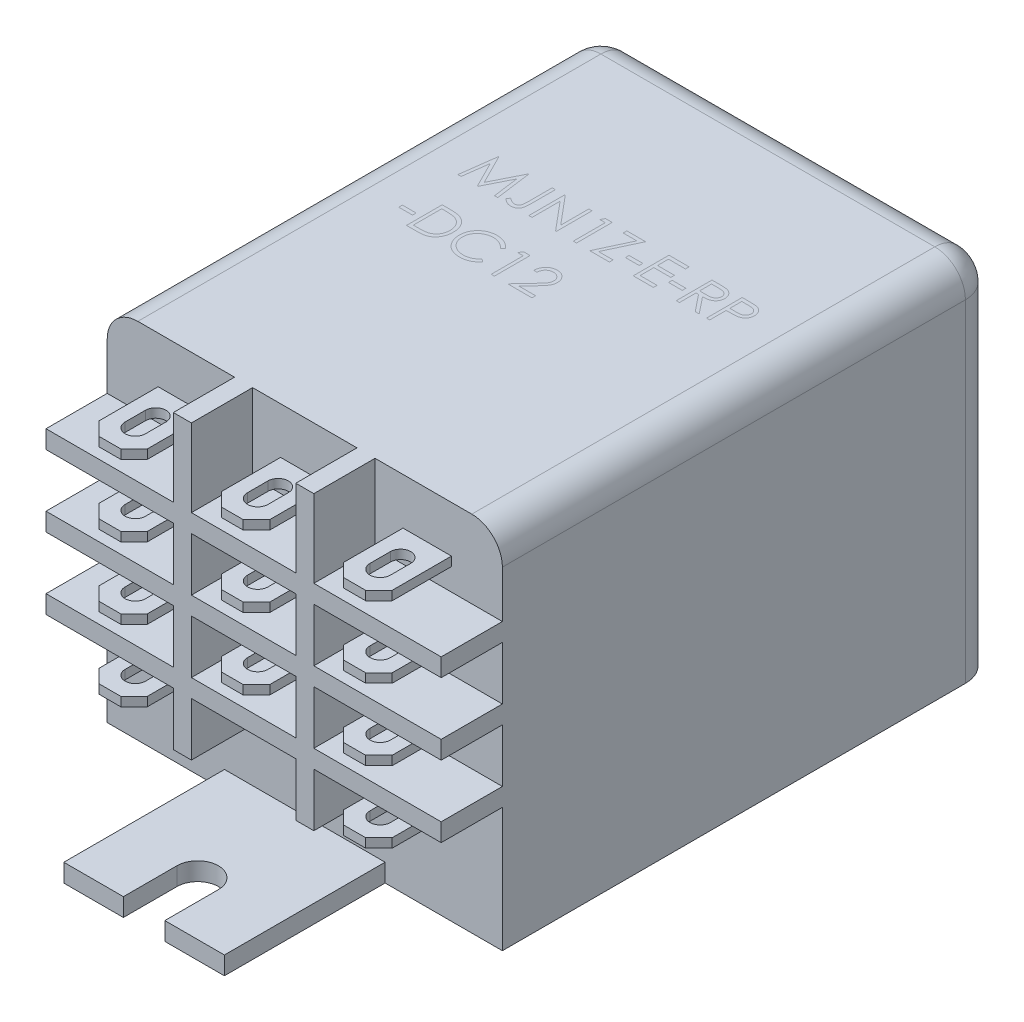
SolidWorks part; units mm, degrees
material "ABS"
ref_plane "Ground_Plane" through (0, 0, 0) normal (0, 0, 1) x (1, 0, 0)
ref_plane "VehicleCentre_Plane" through (0, 0, 0) normal (0, 1, 0) x (1, 0, 0)
ref_plane "FrontAxle_Plane" through (0, 0, 0) normal (1, 0, 0) x (0, 0, -1)
sketch "Sketch1" plane through (0, 0, 0) normal (0, 1, 0) x (1, 0, 0)
  line L1 (19.365, 24.19) -> (-19.365, 24.19)
  line L2 (19.365, 24.19) -> (19.365, -24.19)
  line L3 (19.365, -24.19) -> (-19.365, -24.19)
  line L4 (-19.365, 24.19) -> (-19.365, -24.19)
  line L5 (19.365, 24.19) -> (-19.365, -24.19) construction
  line L6 (19.365, -24.19) -> (-19.365, 24.19) construction
  point P0 (0, 0)
  dimension "D1" = 38.73
  dimension "D2" = 48.38
extrude "Boss-Extrude1" add sketch "Sketch1" along normal blind 35.56
sketch "Sketch2" plane through (0, 0, 0) normal (0, 1, 0) x (1, 0, 0)
  line L0 (-7.87, 24.19) -> (7.87, 24.19)
  line L1 (19.365, 24.19) -> (-19.365, 24.19) construction
  line L2 (7.87, 24.19) -> (7.87, 33.72)
  line L3 (7.87, 33.72) -> (2.03, 33.72)
  line L4 (2.03, 33.72) -> (2.03, 28.81)
  line L5 (-7.87, 24.19) -> (-7.87, 33.72)
  line L6 (-7.87, 33.72) -> (-2.03, 33.72)
  line L7 (-2.03, 33.72) -> (-2.03, 28.81)
  line L8 (7.87, -24.19) -> (-7.87, -24.19)
  line L9 (-7.87, -24.19) -> (-7.87, -39.94)
  line L10 (-7.87, -39.94) -> (-2.03, -39.94)
  line L11 (-2.03, -39.94) -> (-2.03, -34.69)
  line L12 (7.87, -24.19) -> (7.87, -39.94)
  line L13 (7.87, -39.94) -> (2.03, -39.94)
  line L14 (2.03, -39.94) -> (2.03, -34.69)
  line L15 (-19.365, -24.19) -> (19.365, -24.19) construction
  arc A0 (-2.03, 28.81) -> (2.03, 28.81) centre (0, 28.81) ccw
  arc A1 (2.03, -34.69) -> (-2.03, -34.69) centre (0, -34.69) ccw
  dimension "D2" = 2.03
  dimension "D1" = 15.74
  dimension "D3" = 9.53
  dimension "D4" = 10.5
  dimension "D5" = 73.66
  dimension "D6" = 63.5
extrude "Boss-Extrude2" add sketch "Sketch2" along normal blind 1.77
sketch "Sketch3" plane through (0, 0, 24.19) normal (0, 0, 1) x (1, 0, 0)
  line L0 (-19.365, 35.56) -> (19.365, 35.56) construction
  line L1 (-2.3749, 31.0045) -> (2.3749, 31.0045)
  line L2 (-2.3749, 31.0045) -> (-2.3749, 30.1155)
  line L3 (-2.3749, 30.1155) -> (2.3749, 30.1155)
  line L4 (2.3749, 31.0045) -> (2.3749, 30.1155)
  line L5 (-2.3749, 31.0045) -> (2.3749, 30.1155) construction
  line L6 (-2.3749, 30.1155) -> (2.3749, 31.0045) construction
  line L7 (9.6251, 31.0045) -> (9.6251, 30.1155)
  line L8 (9.6251, 31.0045) -> (14.3749, 31.0045)
  line L9 (14.3749, 31.0045) -> (14.3749, 30.1155)
  line L10 (9.6251, 30.1155) -> (14.3749, 30.1155)
  line L11 (9.6251, 24.0045) -> (9.6251, 23.1155)
  line L12 (9.6251, 24.0045) -> (14.3749, 24.0045)
  line L13 (14.3749, 24.0045) -> (14.3749, 23.1155)
  line L14 (9.6251, 23.1155) -> (14.3749, 23.1155)
  line L15 (9.6251, 17.0045) -> (9.6251, 16.1155)
  line L16 (9.6251, 17.0045) -> (14.3749, 17.0045)
  line L17 (14.3749, 17.0045) -> (14.3749, 16.1155)
  line L18 (9.6251, 16.1155) -> (14.3749, 16.1155)
  line L19 (9.6251, 10.0045) -> (9.6251, 9.1155)
  line L20 (9.6251, 10.0045) -> (14.3749, 10.0045)
  line L21 (14.3749, 10.0045) -> (14.3749, 9.1155)
  line L22 (9.6251, 9.1155) -> (14.3749, 9.1155)
  line L23 (-2.3749, 24.0045) -> (-2.3749, 23.1155)
  line L24 (-2.3749, 24.0045) -> (2.3749, 24.0045)
  line L25 (2.3749, 24.0045) -> (2.3749, 23.1155)
  line L26 (-2.3749, 23.1155) -> (2.3749, 23.1155)
  line L27 (-2.3749, 17.0045) -> (-2.3749, 16.1155)
  line L28 (-2.3749, 17.0045) -> (2.3749, 17.0045)
  line L29 (2.3749, 17.0045) -> (2.3749, 16.1155)
  line L30 (-2.3749, 16.1155) -> (2.3749, 16.1155)
  line L35 (-2.3749, 31.0045) -> (9.6251, 31.0045) construction
  line L36 (-2.3749, 31.0045) -> (-2.3749, 24.0045) construction
  line L37 (-14.3749, 31.0045) -> (-14.3749, 30.1155)
  line L38 (-14.3749, 31.0045) -> (-9.6251, 31.0045)
  line L39 (-9.6251, 31.0045) -> (-9.6251, 30.1155)
  line L40 (-14.3749, 30.1155) -> (-9.6251, 30.1155)
  line L41 (-14.3749, 24.0045) -> (-14.3749, 23.1155)
  line L42 (-14.3749, 24.0045) -> (-9.6251, 24.0045)
  line L43 (-9.6251, 24.0045) -> (-9.6251, 23.1155)
  line L44 (-14.3749, 23.1155) -> (-9.6251, 23.1155)
  line L45 (-14.3749, 17.0045) -> (-14.3749, 16.1155)
  line L46 (-14.3749, 17.0045) -> (-9.6251, 17.0045)
  line L47 (-9.6251, 17.0045) -> (-9.6251, 16.1155)
  line L48 (-14.3749, 16.1155) -> (-9.6251, 16.1155)
  line L49 (-14.3749, 10.0045) -> (-14.3749, 9.1155)
  line L50 (-14.3749, 10.0045) -> (-9.6251, 10.0045)
  line L51 (-9.6251, 10.0045) -> (-9.6251, 9.1155)
  line L52 (-14.3749, 9.1155) -> (-9.6251, 9.1155)
  line L53 (-2.3749, 24.0045) -> (-2.3749, 23.1155) [skipped]
  line L54 (-2.3749, 24.0045) -> (2.3749, 24.0045) [skipped]
  line L55 (2.3749, 24.0045) -> (2.3749, 23.1155) [skipped]
  line L56 (-2.3749, 23.1155) -> (2.3749, 23.1155) [skipped]
  line L57 (-2.3749, 17.0045) -> (-2.3749, 16.1155) [skipped]
  line L58 (-2.3749, 17.0045) -> (2.3749, 17.0045) [skipped]
  line L59 (2.3749, 17.0045) -> (2.3749, 16.1155) [skipped]
  line L60 (-2.3749, 16.1155) -> (2.3749, 16.1155) [skipped]
  line L61 (-2.3749, 10.0045) -> (-2.3749, 9.1155) [skipped]
  line L62 (-2.3749, 10.0045) -> (2.3749, 10.0045) [skipped]
  line L63 (2.3749, 10.0045) -> (2.3749, 9.1155) [skipped]
  line L64 (-2.3749, 9.1155) -> (2.3749, 9.1155) [skipped]
  line L65 (-2.3749, 31.0045) -> (-14.3749, 31.0045) construction
  line L66 (-2.3749, 31.0045) -> (-2.3749, 24.0045) construction
  line L67 (-2.3749, 9.1155) -> (2.3749, 9.1155) [skipped]
  line L68 (-2.3749, 10.0045) -> (-2.3749, 9.1155) [skipped]
  line L69 (-2.3749, 10.0045) -> (2.3749, 10.0045) [skipped]
  line L70 (2.3749, 10.0045) -> (2.3749, 9.1155) [skipped]
  point P0 (0, 30.56)
  dimension "D1" = 0.889
  dimension "D2" = 4.7498
  dimension "D3" = 5
  dimension "D6" = 12
  dimension "D7" = 7
  dimension "D10" = 12
  dimension "D11" = 7
  dimension "D4" = 2
  dimension "D5" = 4
  dimension "D8" = 2
  dimension "D9" = 4
extrude "Boss-Extrude3" add sketch "Sketch3" along normal blind 7.11 separate body
sketch "Sketch4" plane through (0, 31.0045, 0) normal (0, 1, 0) x (1, 0, 0)
  line L0 (-14.8749, -29.5) -> (-12.5749, -31.8)
  line L1 (-12.5749, -31.8) -> (-11.4251, -31.8)
  line L2 (-11.4251, -31.8) -> (-9.1251, -29.5)
  line L3 (-9.1251, -29.5) -> (-9.1251, -32.8)
  line L4 (-9.1251, -32.8) -> (-14.8749, -32.8)
  line L5 (-14.8749, -32.8) -> (-14.8749, -29.5)
  line L6 (-9.6251, -31.3) -> (-14.3749, -31.3) construction
  line L7 (-14.3749, -31.3) -> (-14.3749, -24.19) construction
  line L8 (-9.6251, -31.3) -> (-9.6251, -24.19) construction
  line L9 (-12, -26.8) -> (-12, -28.8) construction
  line L10 (-11, -26.8) -> (-11, -28.8)
  line L11 (-13, -26.8) -> (-13, -28.8)
  line L12 (-2.8749, -32.8) -> (-2.8749, -29.5)
  line L13 (-2.8749, -29.5) -> (-0.5749, -31.8)
  line L14 (-0.5749, -31.8) -> (0.5749, -31.8)
  line L15 (0.5749, -31.8) -> (2.8749, -29.5)
  line L16 (2.8749, -29.5) -> (2.8749, -32.8)
  line L17 (2.8749, -32.8) -> (-2.8749, -32.8)
  line L18 (0, -26.8) -> (0, -28.8) construction
  line L19 (1, -26.8) -> (1, -28.8)
  line L20 (-1, -26.8) -> (-1, -28.8)
  line L21 (9.1251, -32.8) -> (9.1251, -29.5)
  line L22 (9.1251, -29.5) -> (11.4251, -31.8)
  line L23 (11.4251, -31.8) -> (12.5749, -31.8)
  line L24 (12.5749, -31.8) -> (14.8749, -29.5)
  line L25 (14.8749, -29.5) -> (14.8749, -32.8)
  line L26 (14.8749, -32.8) -> (9.1251, -32.8)
  line L27 (12, -26.8) -> (12, -28.8) construction
  line L28 (13, -26.8) -> (13, -28.8)
  line L29 (11, -26.8) -> (11, -28.8)
  line L30 (-14.8749, -32.8) -> (-2.8749, -32.8) construction
  arc A0 (-11, -26.8) -> (-13, -26.8) centre (-12, -26.8) ccw
  arc A1 (-13, -28.8) -> (-11, -28.8) centre (-12, -28.8) ccw
  arc A2 (1, -26.8) -> (-1, -26.8) centre (0, -26.8) ccw
  arc A3 (-1, -28.8) -> (1, -28.8) centre (0, -28.8) ccw
  arc A4 (13, -26.8) -> (11, -26.8) centre (12, -26.8) ccw
  arc A5 (11, -28.8) -> (13, -28.8) centre (12, -28.8) ccw
  point P10 (-12, -27.8)
  point P19 (-12, -31.3)
  point P28 (0, -27.8)
  point P41 (12, -27.8)
  dimension "D7" = 1
  dimension "D1" = 0.5
  dimension "D2" = 0.5
  dimension "D3" = 135
  dimension "D4" = 0.5
  dimension "D5" = 1.8
  dimension "D6" = 1
  dimension "D8" = 2
  dimension "D9" = 3.5
  dimension "D11" = 12
  dimension "D10" = 3
extrude "Cut-Extrude1" cut sketch "Sketch4" against normal blind 26
sketch "Sketch5" plane through (0, 0, 24.19) normal (0, 0, 1) x (1, 0, 0)
  line L0 (-19.365, 27.945) -> (-6.885, 27.945)
  line L1 (-19.365, 35.56) -> (-19.365, 0) construction
  line L2 (-6.885, 27.945) -> (-6.885, 35.56)
  line L3 (-19.365, 35.56) -> (19.365, 35.56) construction
  line L4 (-6.885, 35.56) -> (-5.115, 35.56)
  line L5 (-5.115, 35.56) -> (-5.115, 27.945)
  line L6 (-5.115, 27.945) -> (5.115, 27.945)
  line L7 (5.115, 27.945) -> (5.115, 35.56)
  line L8 (5.115, 35.56) -> (6.885, 35.56)
  line L9 (6.885, 35.56) -> (6.885, 27.945)
  line L10 (6.885, 27.945) -> (19.365, 27.945)
  line L11 (19.365, 35.56) -> (19.365, 0) construction
  line L12 (19.365, 27.945) -> (19.365, 26.175)
  line L13 (19.365, 26.175) -> (6.885, 26.175)
  line L14 (6.885, 26.175) -> (6.885, 20.945)
  line L15 (6.885, 20.945) -> (19.365, 20.945)
  line L16 (19.365, 20.945) -> (19.365, 19.175)
  line L17 (19.365, 19.175) -> (6.885, 19.175)
  line L18 (6.885, 19.175) -> (6.885, 13.945)
  line L19 (6.885, 13.945) -> (19.365, 13.945)
  line L20 (19.365, 13.945) -> (19.365, 12.175)
  line L21 (19.365, 12.175) -> (6.885, 12.175)
  line L22 (6.885, 12.175) -> (6.885, 6.945)
  line L23 (6.885, 6.945) -> (5.115, 6.945)
  line L24 (5.115, 6.945) -> (5.115, 12.175)
  line L25 (5.115, 12.175) -> (-5.115, 12.175)
  line L26 (-5.115, 12.175) -> (-5.115, 6.945)
  line L27 (-5.115, 6.945) -> (-6.885, 6.945)
  line L28 (-6.885, 6.945) -> (-6.885, 12.175)
  line L29 (-6.885, 12.175) -> (-19.365, 12.175)
  line L30 (-19.365, 12.175) -> (-19.365, 13.945)
  line L31 (-19.365, 13.945) -> (-6.885, 13.945)
  line L32 (-6.885, 13.945) -> (-6.885, 19.175)
  line L33 (-6.885, 19.175) -> (-19.365, 19.175)
  line L34 (-19.365, 19.175) -> (-19.365, 20.945)
  line L35 (-19.365, 20.945) -> (-6.885, 20.945)
  line L36 (-6.885, 20.945) -> (-6.885, 26.175)
  line L37 (-6.885, 26.175) -> (-19.365, 26.175)
  line L38 (-19.365, 26.175) -> (-19.365, 27.945)
  line L40 (-5.115, 26.175) -> (5.115, 26.175)
  line L41 (-5.115, 26.175) -> (-5.115, 20.945)
  line L42 (-5.115, 20.945) -> (5.115, 20.945)
  line L43 (5.115, 26.175) -> (5.115, 20.945)
  line L44 (-5.115, 26.175) -> (5.115, 20.945) construction
  line L45 (-5.115, 20.945) -> (5.115, 26.175) construction
  line L46 (-5.115, 19.175) -> (5.115, 19.175)
  line L47 (-5.115, 19.175) -> (-5.115, 13.945)
  line L48 (-5.115, 13.945) -> (5.115, 13.945)
  line L49 (5.115, 19.175) -> (5.115, 13.945)
  line L50 (-5.115, 19.175) -> (5.115, 13.945) construction
  line L51 (-5.115, 13.945) -> (5.115, 19.175) construction
  line L52 (-13.0749, 30.1155) -> (-13.0749, 24.0045) construction
  line L53 (-9.6251, 31.0045) -> (-2.3749, 31.0045) construction
  line L54 (-9.6251, 31.0045) -> (-9.6251, 30.1155) construction
  line L56 (-13.0749, 30.1155) -> (-14.3749, 30.1155) construction
  line L57 (-13.0749, 23.1155) -> (-14.3749, 23.1155) construction
  line L58 (-13.0749, 16.1155) -> (-14.3749, 16.1155) construction
  line L59 (2.3749, 31.0045) -> (2.3749, 30.1155) construction
  point P46 (0, 23.56)
  point P51 (0, 16.56)
  point P58 (-13.0749, 27.06)
  point P59 (-19.365, 27.06)
  point P65 (-6, 35.56)
  point P66 (-9.6251, 30.56)
  point P70 (-13.7249, 30.1155)
  point P75 (-6, 31.0045)
extrude "Boss-Extrude4" add sketch "Sketch5" along normal blind 6
fillet "Fillet1" radius 6 2 edges at (7.87, 0.885, -24.19) (-7.87, 0.885, -24.19)
fillet "Fillet2" radius 3 5 edges at (-19.365, 35.56, 0) (19.365, 35.56, 0) (-19.365, 17.78, -24.19) (19.365, 17.78, -24.19) (0, 35.56, -24.19)
sketch "Sketch6" plane through (0, 35.56, 0) normal (0, 1, 0) x (1, 0, 0)
  text T0 "MJN1Z-E-RP\r\n-DC12"
split line "Split Line1"
equation "\"D3@Sketch5\"=\"D2@Sketch5\""
equation "\"D4@Sketch5\"=\"D2@Sketch5\""
equation "\"D6@Sketch5\"=\"D5@Sketch5\""
